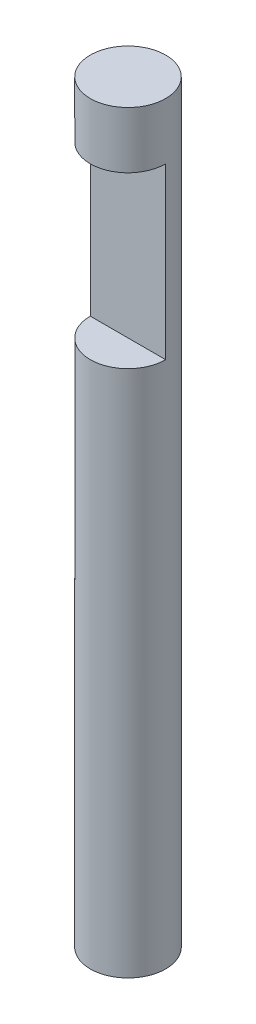
SolidWorks part; units mm, degrees
material "Cast Alloy Steel"
ref_plane "Front Plane" through (0, 0, 0) normal (0, 0, 1) x (1, 0, 0)
ref_plane "Top Plane" through (0, 0, 0) normal (0, 1, 0) x (1, 0, 0)
ref_plane "Right Plane" through (0, 0, 0) normal (1, 0, 0) x (0, 0, -1)
sketch "Sketch1" plane through (0, 0, 0) normal (0, 1, 0) x (1, 0, 0)
  circle A0 centre (0, 0) radius 2
  dimension "D1" = 4
extrude "Boss-Extrude1" add sketch "Sketch1" along normal blind 28
sketch "Sketch2" plane through (0, 28, 0) normal (0, 1, 0) x (1, 0, 0)
  line L0 (-2, 0) -> (2, 0)
  circle A0 centre (0, 0) radius 2 construction
  arc A1 (-2, 0) -> (2, 0) centre (0, 0) cw
extrude "Boss-Extrude2" add sketch "Sketch2" along normal blind 9
sketch "Sketch3" plane through (0, 37, 0) normal (0, 1, 0) x (1, 0, 0)
  circle A0 centre (0, 0) radius 2
extrude "Boss-Extrude3" add sketch "Sketch3" along normal blind 3
